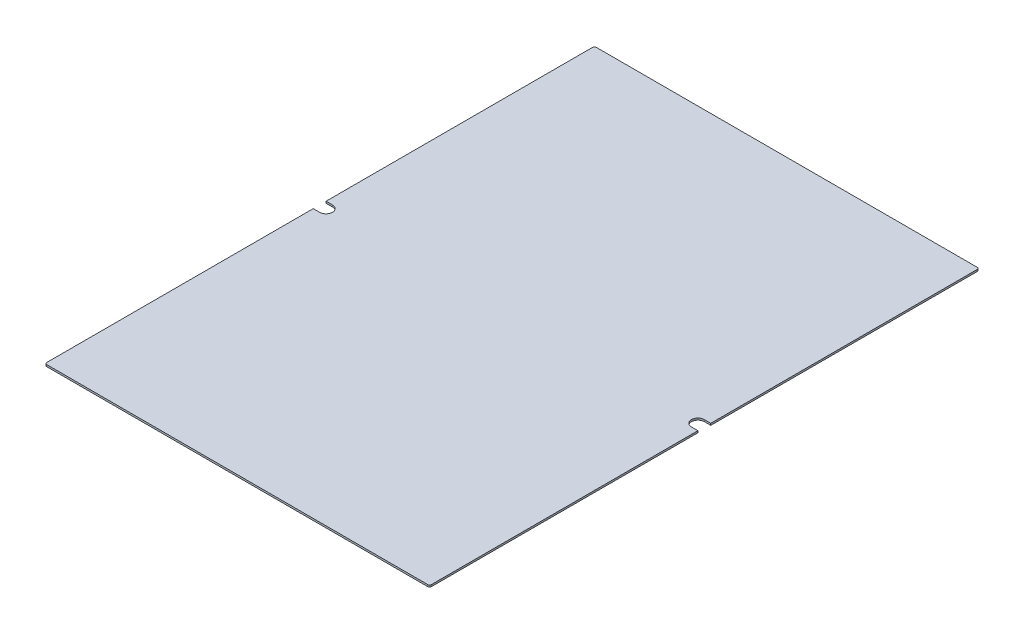
SolidWorks part; units mm, degrees
ref_plane "Alzado" through (0, 0, 0) normal (0, 0, 1) x (1, 0, 0)
ref_plane "Planta" through (0, 0, 0) normal (0, 1, 0) x (1, 0, 0)
ref_plane "Vista lateral" through (0, 0, 0) normal (1, 0, 0) x (0, 0, -1)
sketch "Croquis1" plane through (0, 0, 0) normal (0, 1, 0) x (1, 0, 0)
  line L0 (0, 150) -> (210, 150) construction
  line L1 (0, 0) -> (210, 0)
  line L2 (0, 0) -> (0, 146.5)
  line L3 (0, 300) -> (210, 300)
  line L4 (210, 0) -> (210, 146.5)
  line L5 (3.5, 153.5) -> (0, 153.5)
  line L6 (3.5, 146.5) -> (0, 146.5)
  line L7 (0, 153.5) -> (0, 300)
  line L8 (105, 300) -> (105, 0) construction
  line L9 (206.5, 146.5) -> (210, 146.5)
  line L10 (206.5, 153.5) -> (210, 153.5)
  line L11 (210, 153.5) -> (210, 300)
  arc A0 (3.5, 146.5) -> (3.5, 153.5) centre (3.5, 150) ccw
  arc A1 (206.5, 146.5) -> (206.5, 153.5) centre (206.5, 150) cw
  dimension "D3" = 7
  dimension "D1" = 300
  dimension "D2" = 210
  dimension "D4" = 3.5
extrude "Saliente-Extruir1" add sketch "Croquis1" along normal blind 1
fillet "Redondeo1" radius 1 4 edges at (0, 0.5, 0) (210, 0.5, 0) (210, 0.5, -300) (0, 0.5, -300)
